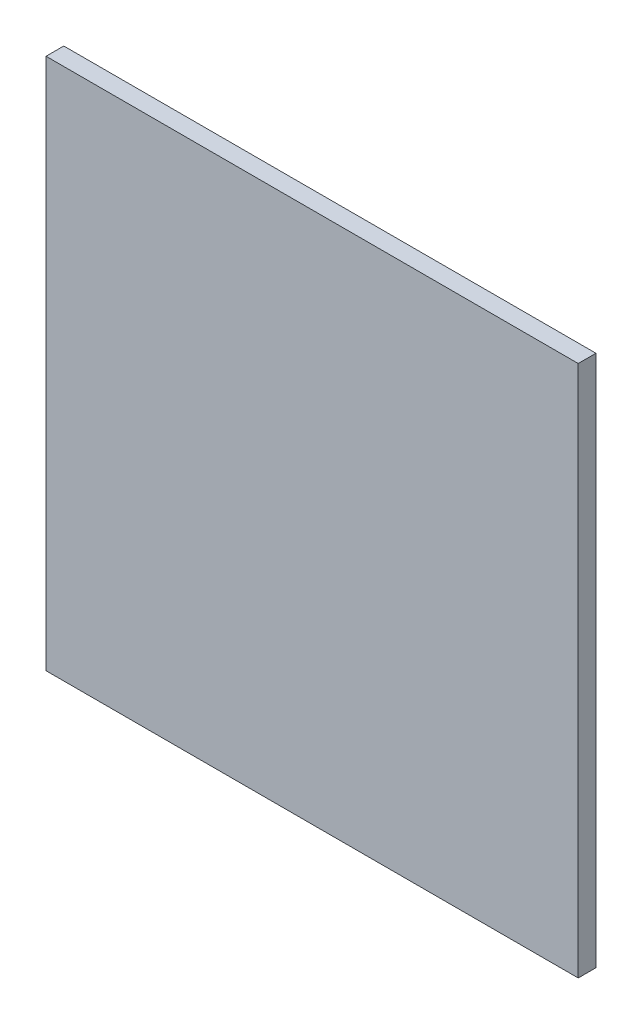
SolidWorks part; units mm, degrees
material "Chêne"
ref_plane "Plan de face" through (0, 0, 0) normal (0, 0, 1) x (1, 0, 0)
ref_plane "Plan de dessus" through (0, 0, 0) normal (0, 1, 0) x (1, 0, 0)
ref_plane "Plan de droite" through (0, 0, 0) normal (1, 0, 0) x (0, 0, -1)
sketch "Esquisse1" plane through (0, 0, 0) normal (0, 0, 1) x (1, 0, 0)
  line L1 (-190.5, -190.5) -> (190.5, -190.5)
  line L2 (-190.5, -190.5) -> (-190.5, 190.5)
  line L3 (-190.5, 190.5) -> (190.5, 190.5)
  line L4 (190.5, -190.5) -> (190.5, 190.5)
  line L5 (-190.5, -190.5) -> (190.5, 190.5) construction
  line L6 (-190.5, 190.5) -> (190.5, -190.5) construction
  point P0 (0, 0)
  dimension "D1" = 381
  dimension "D2" = 381
extrude "Boss.-Extru.1" add sketch "Esquisse1" along normal blind 12.7
